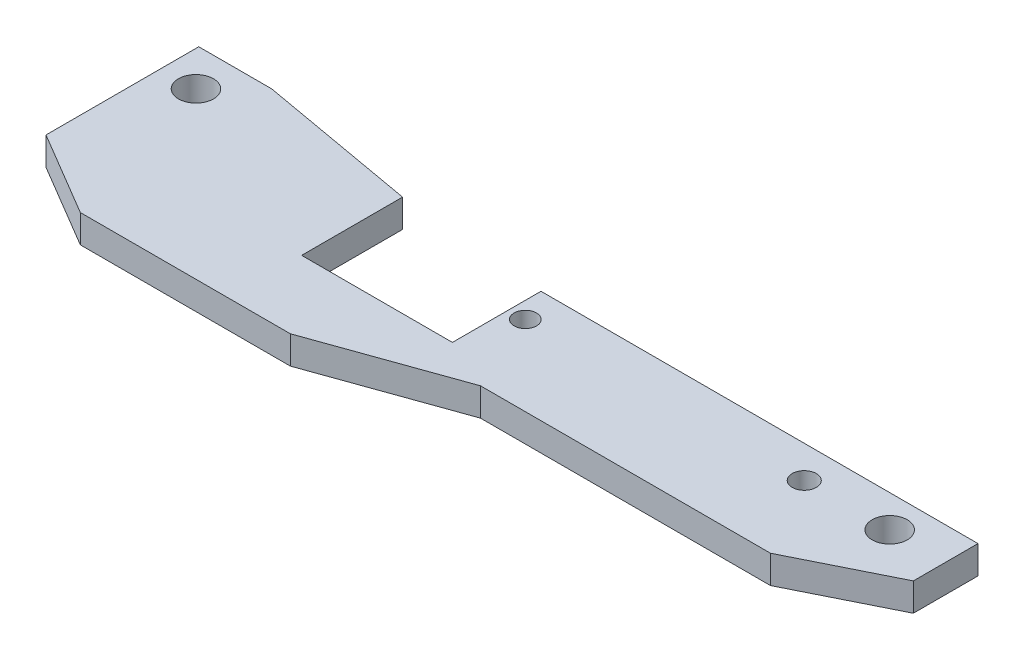
SolidWorks part; units mm, degrees
ref_plane "Front Plane" through (0, 0, 0) normal (0, 0, 1) x (1, 0, 0)
ref_plane "Top Plane" through (0, 0, 0) normal (0, 1, 0) x (1, 0, 0)
ref_plane "Right Plane" through (0, 0, 0) normal (1, 0, 0) x (0, 0, -1)
sketch "Sketch1" plane through (0, 0, 0) normal (0, 1, 0) x (1, 0, 0)
  line L0 (-3.175, 3.429) -> (-3.175, -10.414)
  line L2 (36.195, -10.414) -> (23.4975, -14.9463)
  line L3 (62.474, -10.414) -> (36.195, -10.414)
  line L4 (71.12, -0.254) -> (71.12, -6.1129)
  line L5 (-3.175, 3.429) -> (3.429, 3.429)
  line L6 (3.429, 3.429) -> (24.1459, -0.254)
  line L11 (71.12, -6.1129) -> (62.474, -10.414)
  line L12 (23.4975, -14.9463) -> (4.4672, -14.9463)
  line L14 (4.4672, -14.9463) -> (-3.175, -10.414)
  line L17 (24.1459, -0.254) -> (71.12, -0.254)
  circle A0 centre (33.02, -3.175) radius 1.016
  circle A1 centre (66.04, -3.175) radius 1.5875
  circle A2 centre (0, 0) radius 1.5875
  circle A3 centre (58.2966, -3.175) radius 1.0922
  dimension "D2" = 33.02
  dimension "D6" = 66.04
  dimension "D7" = 7.6422
  dimension "D8" = 3.683
  dimension "D5" = 14.9463
  dimension "D9" = 3.175
  dimension "D19" = 2.1844
  dimension "D13" = 3.175
  dimension "D3" = 3.175
  dimension "D11" = 2.032
  dimension "D4" = 243.551
  dimension "D10" = 4.5323
  dimension "D12" = 19.0303
  dimension "D14" = 3.429
  dimension "D15" = 10.16
  dimension "D16" = 24.1459
  dimension "D17" = 36.195
  dimension "D18" = 58.2966
  dimension "D20" = 62.474
  dimension "D21" = 71.12
extrude "Boss-Extrude1" add sketch "Sketch1" along normal blind 2.54
sketch "Sketch2" plane through (0, 0, 0) normal (0, -1, 0) x (1, 0, 0)
  line L1 (31.52, 8.2802) -> (17.8579, 8.2802)
  line L2 (31.52, 8.2802) -> (31.52, -1.4923)
  line L3 (31.52, -1.4923) -> (17.8579, -1.4923)
  line L4 (17.8579, 8.2802) -> (17.8579, -1.4923)
  line L6 (71.12, 0.254) -> (24.1459, 0.254) construction
  circle A0 centre (33.02, 3.175) radius 1.016 construction
  dimension "D3" = 1.5
  dimension "D1" = 13.6621
  dimension "D2" = 9.7725
  dimension "D4" = 1.7463
extrude "Cut-Extrude1" cut sketch "Sketch2" against normal blind 2.54
